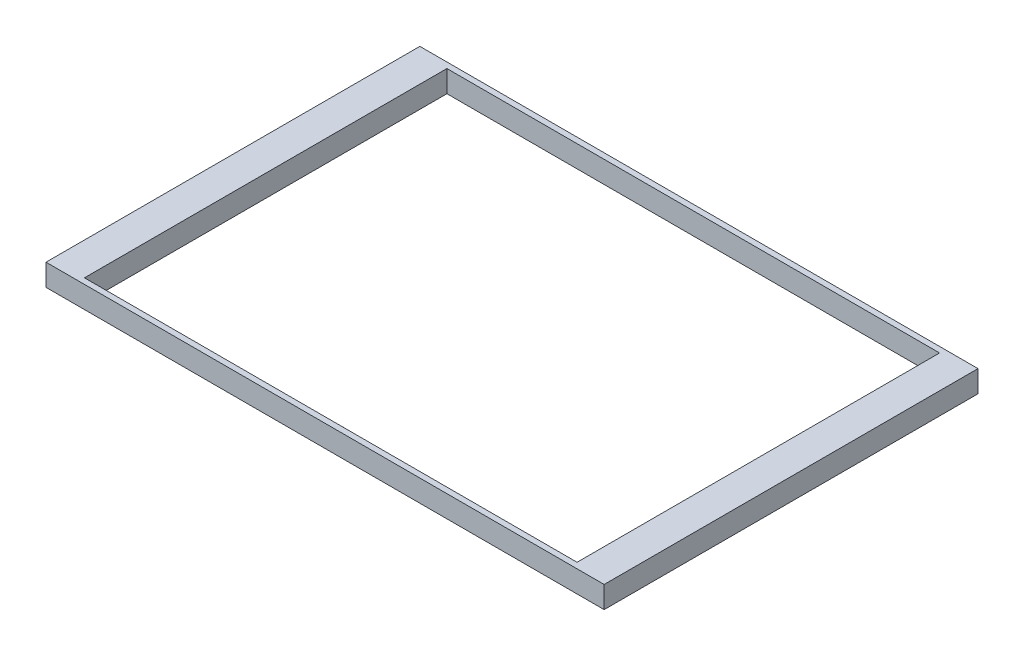
SolidWorks part; units mm, degrees
ref_plane "Front Plane" through (0, 0, 0) normal (0, 0, 1) x (1, 0, 0)
ref_plane "Top Plane" through (0, 0, 0) normal (0, 1, 0) x (1, 0, 0)
ref_plane "Right Plane" through (0, 0, 0) normal (1, 0, 0) x (0, 0, -1)
sketch "Sketch1" plane through (0, 0, 0) normal (0, 1, 0) x (1, 0, 0)
  line L1 (63.9, -42.8) -> (-63.9, -42.8)
  line L2 (63.9, -42.8) -> (63.9, 42.8)
  line L3 (63.9, 42.8) -> (-63.9, 42.8)
  line L4 (-63.9, -42.8) -> (-63.9, 42.8)
  line L5 (63.9, -42.8) -> (-63.9, 42.8) construction
  line L6 (63.9, 42.8) -> (-63.9, -42.8) construction
  point P0 (0, 0)
  dimension "D1" = 127.8
  dimension "D2" = 85.6
extrude "Boss-Extrude1" add sketch "Sketch1" along normal blind 5
ref_plane "Plane1" through (0, 5, 0) normal (0, 1, 0) x (1, 0, 0)
sketch "Sketch2" plane through (0, 5, 0) normal (0, 1, 0) x (1, 0, 0)
  line L1 (56.4, -41.5) -> (-56.4, -41.5)
  line L2 (56.4, -41.5) -> (56.4, 41.5)
  line L3 (56.4, 41.5) -> (-56.4, 41.5)
  line L4 (-56.4, -41.5) -> (-56.4, 41.5)
  line L5 (56.4, -41.5) -> (-56.4, 41.5) construction
  line L6 (56.4, 41.5) -> (-56.4, -41.5) construction
  point P0 (0, 0)
  dimension "D1" = 83
  dimension "D2" = 112.8
extrude "Cut-Extrude1" cut sketch "Sketch2" against normal blind 5
